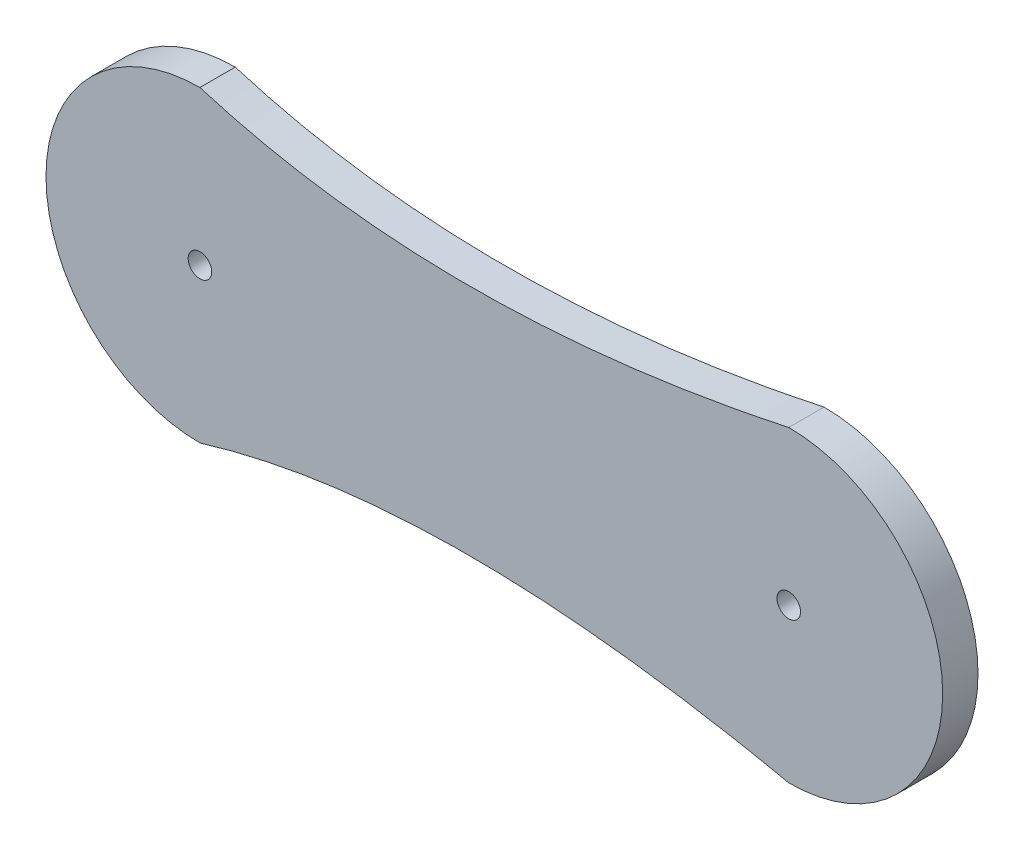
SolidWorks part; units mm, degrees
ref_plane "Front Plane" through (0, 0, 0) normal (0, 0, 1) x (1, 0, 0)
ref_plane "Top Plane" through (0, 0, 0) normal (0, 1, 0) x (1, 0, 0)
ref_plane "Right Plane" through (0, 0, 0) normal (1, 0, 0) x (0, 0, -1)
sketch "Sketch1" plane through (0, 0, 0) normal (0, 0, 1) x (1, 0, 0)
  line L0 (0, 48.486) -> (0, -17.0326) construction
  line L1 (-25, 0) -> (25, 0) construction
  line L2 (-24.7813, 3.393) -> (-3.1073, 1.9959)
  line L3 (-24.7813, -3.393) -> (-3.1073, -1.9959)
  line L4 (24.7813, -3.393) -> (3.1073, -1.9959)
  line L5 (24.7813, 3.393) -> (3.1073, 1.9959)
  line L6 (25, 13.069) -> (25, -13.069) construction
  arc A0 (-24.7813, 3.393) -> (-24.7813, -3.393) centre (-25, 0) ccw
  arc A1 (-3.1073, -1.9959) -> (-3.1073, 1.9959) centre (-3.236, 0) ccw
  arc A2 (3.1073, -1.9959) -> (3.1073, 1.9959) centre (3.236, 0) cw
  arc A3 (24.7813, 3.393) -> (24.7813, -3.393) centre (25, 0) cw
  arc A4 (-12.1884, 2.5812) -> (-12.1884, -2.5812) centre (-25, 0) ccw
  circle A5 centre (25, 0) radius 13.069
  circle A8 centre (25, 0) radius 1
  circle A9 centre (-25, 0) radius 1
  spline S0 degree 2 poles (-25, 13.069) (-4.3275, 6.7524) (25, 13.069) knots 0 0 0 1 1 1
  spline S1 degree 2 poles (-25, -13.069) (-4.3275, -6.7524) (25, -13.069) knots 0 0 0 1 1 1
  dimension "D2" = 6.8
  dimension "D3" = 4
  dimension "D5" = 26.138
  dimension "D8" = 2
  dimension "D1" = 25
  dimension "D4" = 3.236
  dimension "D6" = 48.486
extrude "Boss-Extrude1" add sketch "Sketch1" along normal blind 3 contours A4 S1 L3 A0 L2 S0 | A4 S1 A5 L4 A2 L5 S0 L2 A1 L3 | A5 S1 S0 L5 A3 L4 | A5 L4 A3 L5 A8 | L4 A5 L5 A2 | L3 A1 L2 A0 A9
